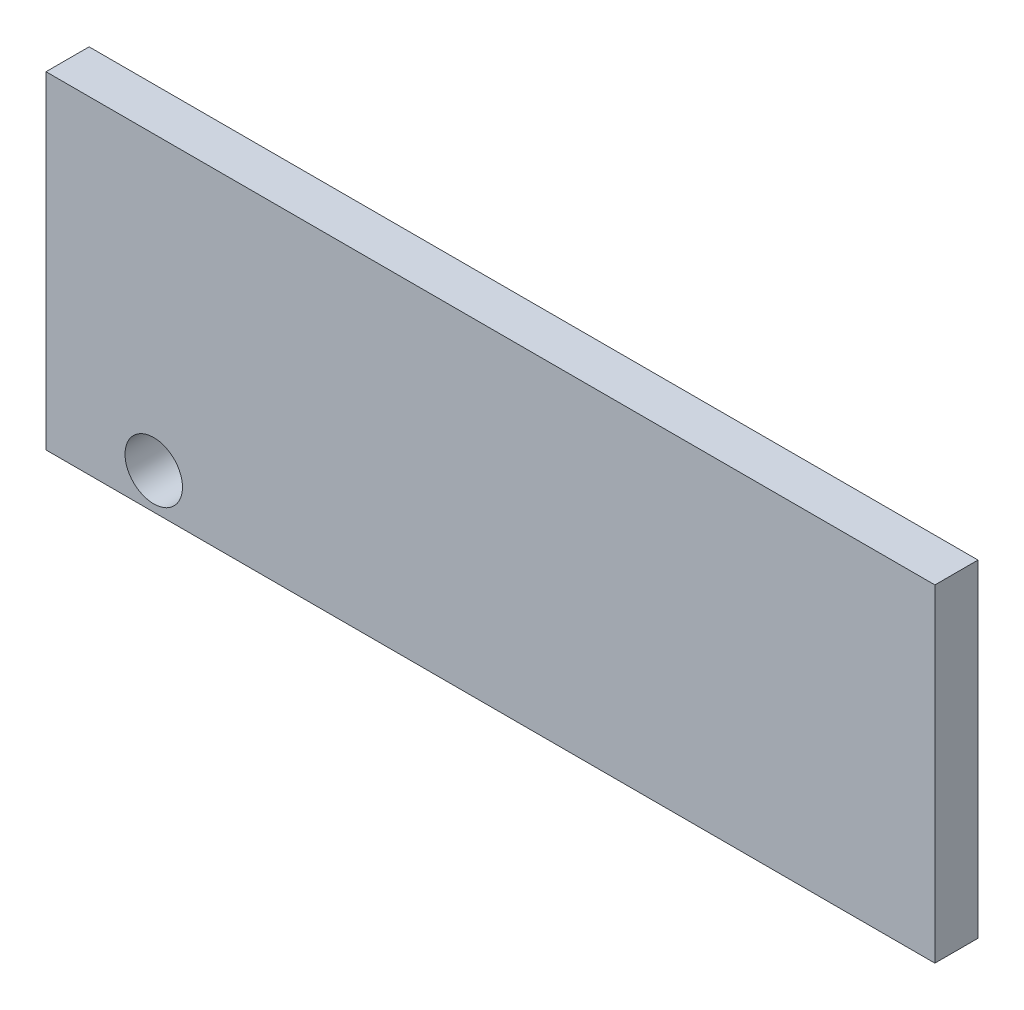
SolidWorks part; units mm, degrees
ref_plane "Plan de face" through (0, 0, 0) normal (0, 0, 1) x (1, 0, 0)
ref_plane "Plan de dessus" through (0, 0, 0) normal (0, 1, 0) x (1, 0, 0)
ref_plane "Plan de droite" through (0, 0, 0) normal (1, 0, 0) x (0, 0, -1)
sketch "Esquisse1" plane through (0, 0, 0) normal (0, 0, 1) x (1, 0, 0)
  line L1 (-61.88, 22.8042) -> (61.88, 22.8042)
  line L2 (-61.88, 22.8042) -> (-61.88, -22.8042)
  line L3 (-61.88, -22.8042) -> (61.88, -22.8042)
  line L4 (61.88, 22.8042) -> (61.88, -22.8042)
  line L5 (-61.88, 22.8042) -> (61.88, -22.8042) construction
  line L6 (-61.88, -22.8042) -> (61.88, 22.8042) construction
  circle A0 centre (-46.88, -17.8042) radius 4
  point P0 (0, 0)
  dimension "D1" = 8
  dimension "D2" = 15
  dimension "D3" = 5
extrude "Boss.-Extru.1" add sketch "Esquisse1" along normal blind 6
